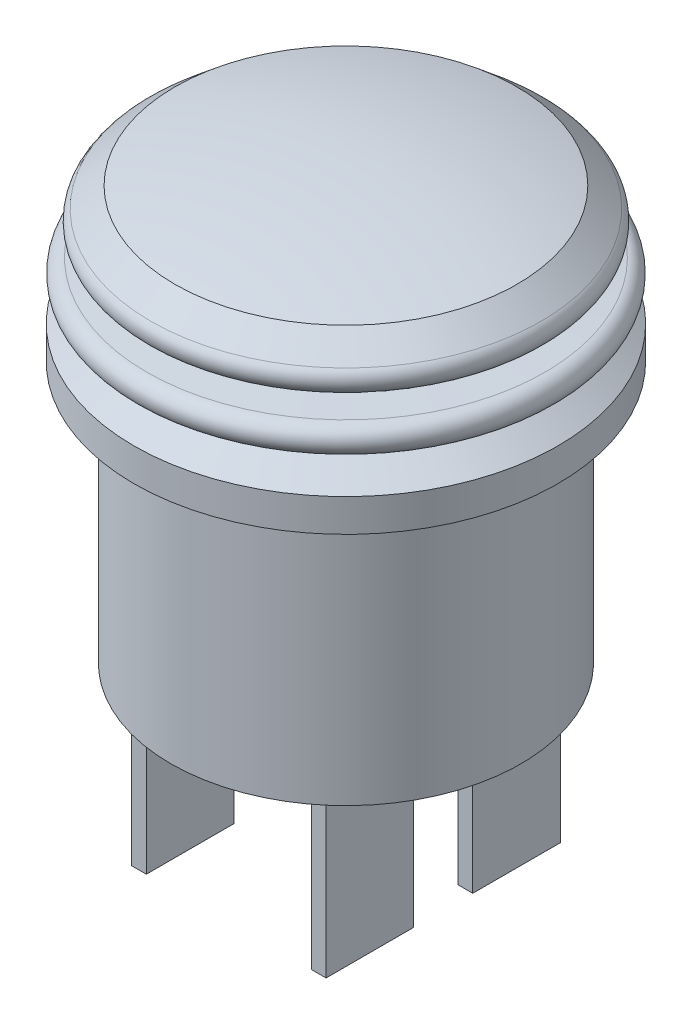
SolidWorks part; units mm, degrees
ref_plane "Front Plane" through (0, 0, 0) normal (0, 0, 1) x (1, 0, 0)
ref_plane "Top Plane" through (0, 0, 0) normal (0, 1, 0) x (1, 0, 0)
ref_plane "Right Plane" through (0, 0, 0) normal (1, 0, 0) x (0, 0, -1)
sketch "Sketch1" plane through (0, 0, 0) normal (0, 0, 1) x (1, 0, 0)
  line L0 (-11.4897, 13.5427) -> (11.5103, 13.5427) construction
  line L1 (0, 40.4284) -> (0, -48.3198) construction
  line L2 (0, -13.242) -> (-9.5, -13.242)
  line L3 (-9.5, -13.242) -> (-9.5, 0.9181)
  line L4 (-9.5, 0.9181) -> (-11.5, 0.9181)
  line L5 (-11.5, 0.9181) -> (-11.5, 2.6939)
  line L6 (-11.5, 2.6939) -> (-9.5927, 3.9912)
  line L7 (-9.5927, 3.9912) -> (-10.9211, 4.3322)
  line L8 (-10.8002, 5.8058) -> (-8.298, 6.0255)
  line L9 (-8.298, 6.0255) -> (-8.298, 6.1842)
  line L10 (-8.298, 6.1842) -> (-10.3169, 6.7944)
  line L11 (-10.5815, 8.0872) -> (-9.2808, 9.1768)
  line L12 (-9.2808, 9.1768) -> (0, 9.1768)
  line L13 (0, 9.1768) -> (0, -13.242)
  arc A0 (-10.9211, 4.3322) -> (-10.8002, 5.8058) centre (-10.7346, 5.0586) cw
  arc A1 (-10.3169, 6.7944) -> (-10.5815, 8.0872) centre (-10.0999, 7.5123) cw
  dimension "D4" = 0.75
  dimension "D1" = 23
  dimension "D2" = 19
  dimension "D3" = 23
revolve "Revolve2" add sketch "Sketch1" angle 360 about L1
sketch "Sketch2" plane through (0, 0, 0) normal (0, 0, 1) x (1, 0, 0)
  line L0 (0, 15.763) -> (0, -17.9549) construction
  line L1 (9.2808, 9.1768) -> (-9.2808, 9.1768) construction
  line L2 (0, 9.1768) -> (-9.2808, 9.1768)
  line L4 (-9.5, 0.9181) -> (9.5, 0.9181) construction
  line L5 (0, 10.4181) -> (0, 9.1768)
  arc A0 (-9.2808, 9.1768) -> (0, 10.4181) centre (0, -24.8993) cw
  point P11 (0, 10.4181)
  dimension "D1" = 9.5
revolve "Revolve3" add sketch "Sketch2" angle 360 about L0
sketch "Sketch3" plane through (0, -13.242, 0) normal (0, -1, 0) x (1, 0, 0)
  line L0 (4.8759, 3.9795) -> (-4.8759, -3.9795) construction
  line L1 (-5.2759, 6.3545) -> (-4.4759, 6.3545)
  line L2 (-5.2759, 6.3545) -> (-5.2759, 1.6045)
  line L3 (-5.2759, 1.6045) -> (-4.4759, 1.6045)
  line L4 (-4.4759, 6.3545) -> (-4.4759, 1.6045)
  line L5 (-5.2759, 6.3545) -> (-4.4759, 1.6045) construction
  line L6 (-5.2759, 1.6045) -> (-4.4759, 6.3545) construction
  line L7 (4.4759, 6.3545) -> (5.2759, 6.3545)
  line L8 (4.4759, 6.3545) -> (4.4759, 1.6045)
  line L9 (4.4759, 1.6045) -> (5.2759, 1.6045)
  line L10 (5.2759, 6.3545) -> (5.2759, 1.6045)
  line L11 (4.4759, 6.3545) -> (5.2759, 1.6045) construction
  line L12 (4.4759, 1.6045) -> (5.2759, 6.3545) construction
  line L13 (4.4759, -1.6045) -> (5.2759, -1.6045)
  line L14 (4.4759, -1.6045) -> (4.4759, -6.3545)
  line L15 (4.4759, -6.3545) -> (5.2759, -6.3545)
  line L16 (5.2759, -1.6045) -> (5.2759, -6.3545)
  line L17 (4.4759, -1.6045) -> (5.2759, -6.3545) construction
  line L18 (4.4759, -6.3545) -> (5.2759, -1.6045) construction
  line L19 (-5.2759, -1.6045) -> (-4.4759, -1.6045)
  line L20 (-5.2759, -1.6045) -> (-5.2759, -6.3545)
  line L21 (-5.2759, -6.3545) -> (-4.4759, -6.3545)
  line L22 (-4.4759, -1.6045) -> (-4.4759, -6.3545)
  line L23 (-5.2759, -1.6045) -> (-4.4759, -6.3545) construction
  line L24 (-5.2759, -6.3545) -> (-4.4759, -1.6045) construction
  line L25 (-4.8759, 3.9795) -> (4.8759, -3.9795) construction
  point P0 (-4.8759, 3.9795)
  point P5 (4.8759, 3.9795)
  point P10 (4.8759, -3.9795)
  point P15 (-4.8759, -3.9795)
  point P24 (0, 0)
  point P25 (0, 0)
  dimension "D1" = 0.8
  dimension "D2" = 4.75
extrude "Boss-Extrude1" add sketch "Sketch3" along normal blind 9
